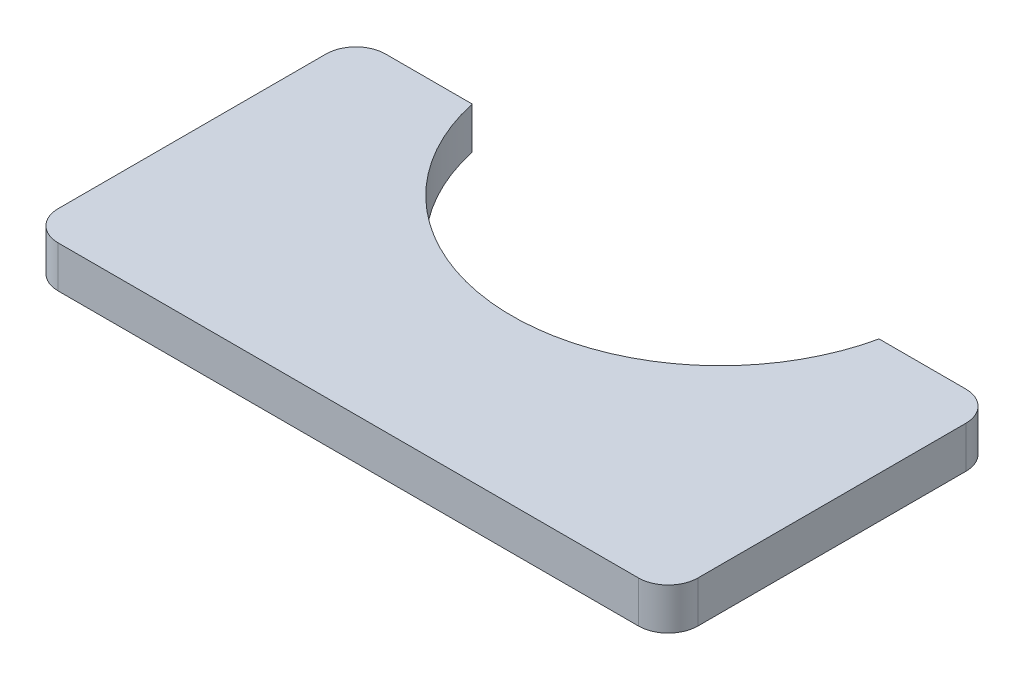
SolidWorks part; units mm, degrees
material "PLA"
ref_plane "Front Plane" through (0, 0, 0) normal (0, 0, 1) x (1, 0, 0)
ref_plane "Top Plane" through (0, 0, 0) normal (0, 1, 0) x (1, 0, 0)
ref_plane "Right Plane" through (0, 0, 0) normal (1, 0, 0) x (0, 0, -1)
sketch "Sketch1" plane through (0, 0, 0) normal (0, 1, 0) x (1, 0, 0)
  line L1 (-21.5, 11) -> (21.5, 11)
  line L2 (-21.5, 11) -> (-21.5, -11)
  line L3 (-21.5, -11) -> (21.5, -11)
  line L4 (21.5, 11) -> (21.5, -11)
  line L5 (-21.5, 11) -> (21.5, -11) construction
  line L6 (-21.5, -11) -> (21.5, 11) construction
  point P0 (0, 0)
  dimension "D1" = 22
  dimension "D2" = 43
extrude "Boss-Extrude1" add sketch "Sketch1" along normal blind 2.8
sketch "Sketch2" plane through (0, 2.8, 0) normal (0, 1, 0) x (1, 0, 0)
  line L0 (21.5, 11) -> (-21.5, 11) construction
  circle A0 centre (0, 14) radius 14
  point P4 (0, 0)
  dimension "D1" = 28
  dimension "D2" = 3
extrude "Cut-Extrude1" cut sketch "Sketch2" against normal through all
fillet "Fillet1" radius 2 4 edges at (21.5, 1.4, -11) (-21.5, 1.4, -11) (-21.5, 1.4, 11) (21.5, 1.4, 11)
